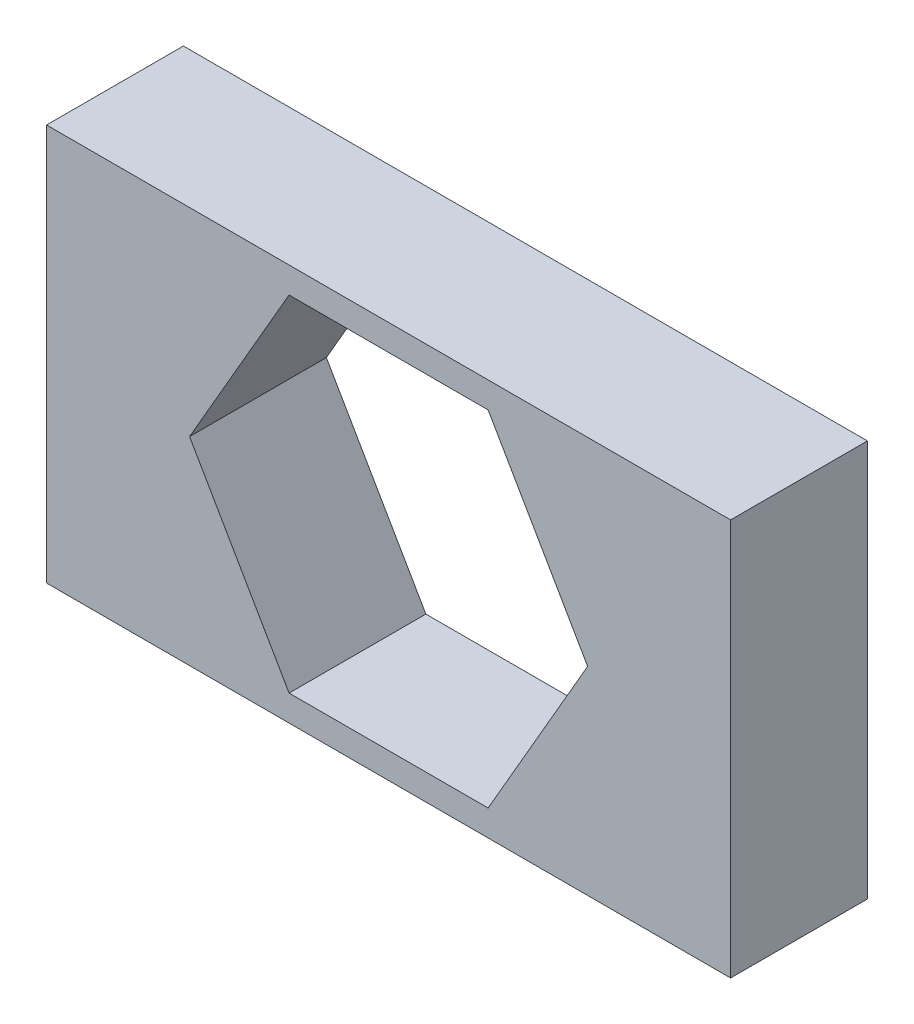
SolidWorks part; units mm, degrees
ref_plane "Plan de face" through (0, 0, 0) normal (0, 0, 1) x (1, 0, 0)
ref_plane "Plan de dessus" through (0, 0, 0) normal (0, 1, 0) x (1, 0, 0)
ref_plane "Plan de droite" through (0, 0, 0) normal (1, 0, 0) x (0, 0, -1)
sketch "Esquisse1" plane through (0, 0, 0) normal (0, 0, 1) x (1, 0, 0)
  line L0 (0, 7.25) -> (25, 7.25) construction
  line L1 (0, 0) -> (25, 0)
  line L2 (0, 0) -> (0, 14.5)
  line L3 (0, 14.5) -> (25, 14.5)
  line L4 (25, 0) -> (25, 14.5)
  line L6 (19.7746, 7.25) -> (16.1373, 13.55)
  line L7 (16.1373, 13.55) -> (8.8627, 13.55)
  line L8 (8.8627, 13.55) -> (5.2254, 7.25)
  line L9 (5.2254, 7.25) -> (8.8627, 0.95)
  line L10 (8.8627, 0.95) -> (16.1373, 0.95)
  line L11 (16.1373, 0.95) -> (19.7746, 7.25)
  circle A0 centre (12.5, 7.25) radius 6.3 construction
  point P8 (19.8901, 8)
  dimension "D1" = 12.6
  dimension "D2" = 14.5
  dimension "D3" = 25
extrude "Boss.-Extru.1" add sketch "Esquisse1" along normal blind 5
